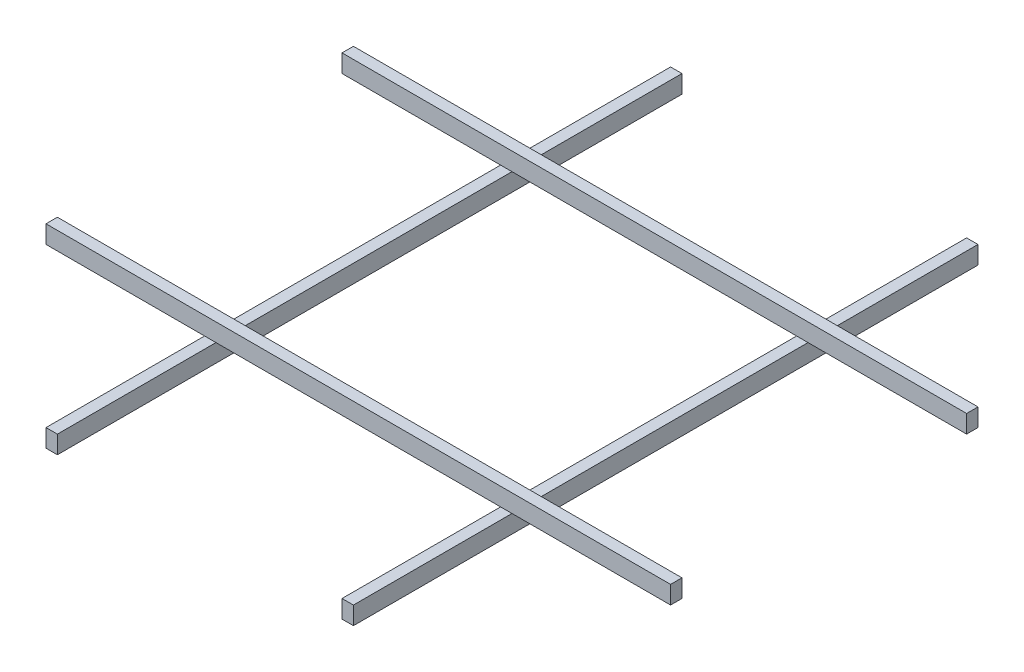
SolidWorks part; units mm, degrees
material "Doug Fir"
ref_plane "Front Plane" through (0, 0, 0) normal (0, 0, 1) x (1, 0, 0)
ref_plane "Top Plane" through (0, 0, 0) normal (0, 1, 0) x (1, 0, 0)
ref_plane "Right Plane" through (0, 0, 0) normal (1, 0, 0) x (0, 0, -1)
sketch "Lower Level" plane through (0, 0, 0) normal (0, 1, 0) x (1, 0, 0)
  line L0 (977.9, 0) -> (977.9, 4876.8)
  line L1 (3289.3, 0) -> (3289.3, 4876.8)
  line L2 (977.9, 2438.4) -> (3289.3, 2438.4) construction
  point P7 (2133.6, 2438.4)
  dimension "D1" = 4876.8
  dimension "D2" = 1155.7
ref_plane "Plane2" through (0, 139.7, 0) normal (0, 1, 0) x (1, 0, 0)
sketch "Sketch12" plane through (0, 139.7, 0) normal (0, 1, 0) x (1, 0, 0)
  line L0 (-304.8, 3594.1) -> (4572, 3594.1)
  line L1 (4572, 1282.7) -> (-304.8, 1282.7)
  line L2 (2133.6, 3594.1) -> (2133.6, 1282.7) construction
  point P0 (2133.6, 2438.4)
  point P6 (2133.6, 1282.7)
  point P7 (2133.6, 3594.1)
  point P10 (2133.6, 2438.4)
  dimension "D1" = 4876.8
  dimension "D2" = 1155.7
other "Profiles 4X6(1)"
ref_plane "Plane1" through (977.9, 0, 0) normal (0, 0, -1) x (-1, 0, 0)
sketch "Sketch1" plane through (977.9, 0, 0) normal (0, 0, -1) x (-1, 0, 0)
  line L1 (-44.45, 69.85) -> (44.45, 69.85)
  line L2 (-44.45, 69.85) -> (-44.45, -69.85)
  line L3 (-44.45, -69.85) -> (44.45, -69.85)
  line L4 (44.45, 69.85) -> (44.45, -69.85)
  line L5 (-44.45, 69.85) -> (44.45, -69.85) construction
  line L6 (-44.45, -69.85) -> (44.45, 69.85) construction
  point P0 (0, 0)
  point P6 (0, 69.85)
  point P7 (0, -69.85)
  point P8 (44.45, 0)
  point P9 (-44.45, 0)
  point P10 (0, 0)
  dimension "D1" = 88.9
  dimension "D2" = 139.7
sketch3d "3DSketch2"
  line L0 (2133.6, 139.7, -2438.4) -> (2133.6, 0, -2438.4)
  line L1 (977.9, 0, -2438.4) -> (3289.3, 0, -2438.4) construction
equation "\"Width\" = 45.5"
equation "\"Length\"=192"
equation "\"D1@Lower Level\"=\"Length\""
equation "\"D2@Lower Level\"=\"Width\""
equation "\"D1@Sketch12\"=\"Length\""
equation "\"D2@Sketch12\"=\"Width\""
